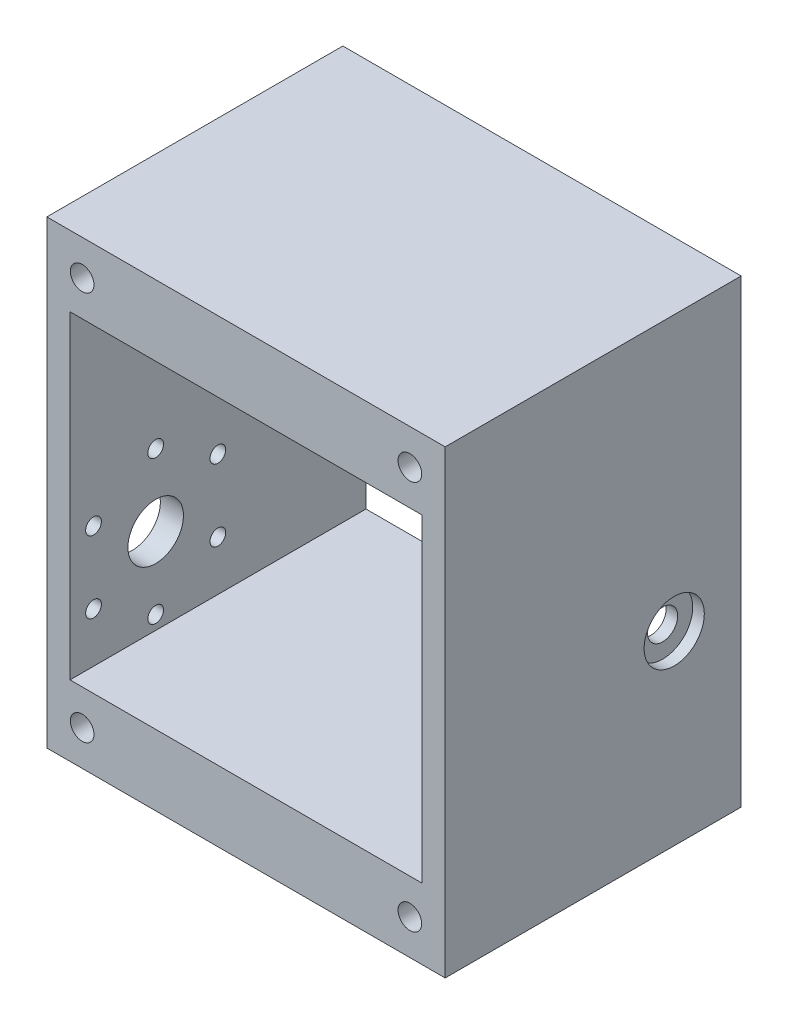
SolidWorks part; units mm, degrees
ref_plane "Front Plane" through (0, 0, 0) normal (0, 0, 1) x (1, 0, 0)
ref_plane "Top Plane" through (0, 0, 0) normal (0, 1, 0) x (1, 0, 0)
ref_plane "Right Plane" through (0, 0, 0) normal (1, 0, 0) x (0, 0, -1)
sketch "Sketch1" plane through (0, 0, 0) normal (0, 0, 1) x (1, 0, 0)
  line L1 (-43, -49.657) -> (43, -49.657)
  line L2 (-43, -49.657) -> (-43, 49.657)
  line L3 (-43, 49.657) -> (43, 49.657)
  line L4 (43, -49.657) -> (43, 49.657)
  line L5 (-43, -49.657) -> (43, 49.657) construction
  line L6 (-43, 49.657) -> (43, -49.657) construction
  point P0 (0, 0)
  dimension "D1" = 86
  dimension "D2" = 99.314
extrude "Boss-Extrude1" add sketch "Sketch1" along normal blind 63.9031
sketch "Sketch2" plane through (0, 0, 63.9031) normal (0, 0, 1) x (1, 0, 0)
  line L0 (-43, 49.657) -> (-43, -49.657) construction
  line L1 (-38, -34.417) -> (38, -34.417)
  line L2 (-38, -34.417) -> (-38, 34.417)
  line L3 (-38, 34.417) -> (38, 34.417)
  line L4 (38, -34.417) -> (38, 34.417)
  line L5 (-38, -34.417) -> (38, 34.417) construction
  line L6 (-38, 34.417) -> (38, -34.417) construction
  line L7 (43, 49.657) -> (-43, 49.657) construction
  point P0 (0, 0)
  dimension "D1" = 5
  dimension "D2" = 15.24
extrude "Cut-Extrude1" cut sketch "Sketch2" against normal through all
hole_wizard "Ø6.5 (6.5) Diameter Hole1" positions "Sketch3" profile "Sketch4" hole size "Ø6.5" standard "ANSI Metric"
sketch "Sketch3" plane through (43, 0, 0) normal (1, 0, 0) x (0, 0, -1)
  line L0 (0, -49.657) -> (0, 49.657) construction
  line L1 (0, 34.417) -> (-63.9031, 34.417) construction
  point P0 (-14.4502, -9.525)
  dimension "D1" = 14.4502
  dimension "D2" = 43.942
sketch "Sketch4" plane through (43, -9.525, 14.4502) normal (0, 1, 0) x (0, 0, -1)
  line L0 (0, 0) -> (0, 5)
  line L1 (0, 5) -> (3.25, 5)
  line L2 (3.25, 5) -> (3.25, 0)
  line L5 (3.25, 0) -> (0, 0)
  line L11 (0, -6.35) -> (0, 107.95) construction
  dimension "Thru Hole Dia." = 6.5
  dimension "Thru Hole Depth" = 5
sketch "Sketch5" plane through (-43, 0, 0) normal (-1, 0, 0) x (0, 0, 1)
  line L0 (63.9031, 49.657) -> (63.9031, -49.657) construction
  line L1 (0, -34.417) -> (63.9031, -34.417) construction
  point P0 (45.4031, -15.917)
  dimension "D1" = 18.5
  dimension "D2" = 18.5
hole_wizard "Ø12.0 (12) Diameter Hole1" positions "Sketch6" profile "Sketch7" hole size "Ø12.0" standard "ANSI Metric"
sketch "Sketch6" plane through (-43, 0, 0) normal (-1, 0, 0) x (0, 0, 1)
  point P0 (45.4031, -15.917)
sketch "Sketch7" plane through (-43, -15.917, 45.4031) normal (0, 1, 0) x (0, 0, 1)
  line L0 (0, 0) -> (0, 5)
  line L1 (0, 5) -> (6, 5)
  line L2 (6, 5) -> (6, 0)
  line L5 (6, 0) -> (0, 0)
  line L11 (0, -6.35) -> (0, 107.95) construction
  dimension "Thru Hole Dia." = 12
  dimension "Thru Hole Depth" = 5
hole_wizard "CSK for M3 Flat Head Machine Screw1" positions "Sketch8" profile "Sketch9" countersink size "M3" standard "ANSI Metric"
sketch "Sketch8" plane through (-43, 0, 0) normal (-1, 0, 0) x (0, 0, 1)
  line L0 (45.4031, -15.917) -> (45.4031, -0.417) construction
  point P0 (45.4031, -0.417)
  point P12 (58.8265, -8.167)
  point P13 (58.8265, -23.667)
  point P14 (45.4031, -31.417)
  point P15 (31.9797, -23.667)
  point P16 (31.9797, -8.167)
  dimension "D2" = 15.5
  dimension "D1" = 6
sketch "Sketch9" plane through (-43, -0.417, 45.4031) normal (0, 1, 0) x (0, 0, 1)
  line L0 (0, 0) -> (0, 5)
  line L1 (0, 5) -> (1.7, 5)
  line L2 (1.7, 5) -> (1.7, 1.45)
  line L3 (1.7, 1.45) -> (3.15, 0)
  line L5 (3.15, 0) -> (0, 0)
  line L6 (-1.7, 1.45) -> (-3.15, 0) construction
  line L11 (0, -6.35) -> (0, 107.95) construction
  dimension "Thru Hole Dia." = 3.4
  dimension "Thru Hole Depth" = 5
  dimension "Near C'Sink Dia." = 6.3
  dimension "Near C'Sink Angle" = 90
hole_wizard "#10 Clearance Hole1" positions "Sketch10" profile "Sketch11" hole size "#10" standard "ANSI Inch" end condition through all
sketch "Sketch10" plane through (0, 0, 63.9031) normal (0, 0, 1) x (1, 0, 0)
  line L0 (-43, 49.657) -> (-43, -49.657) construction
  line L1 (43, 49.657) -> (-43, 49.657) construction
  line L2 (43, -49.657) -> (43, 49.657) construction
  line L3 (-43, -49.657) -> (43, -49.657) construction
  point P0 (-35.38, 42.037)
  point P2 (35.38, 42.037)
  point P4 (-35.38, -42.037)
  point P6 (35.38, -42.037)
  dimension "D1" = 7.62
  dimension "D2" = 7.62
  dimension "D3" = 7.62
  dimension "D4" = 7.62
sketch "Sketch11" plane through (-35.38, 42.037, 63.9031) normal (1, 0, 0) x (0, -1, 0)
  line L0 (0, 0) -> (0, 63.9031)
  line L1 (0, 63.9031) -> (2.5527, 63.9031)
  line L2 (2.5527, 63.9031) -> (2.5527, 0)
  line L5 (2.5527, 0) -> (0, 0)
  line L11 (0, -6.35) -> (0, 107.95) construction
  dimension "Thru Hole Dia." = 5.1054
  dimension "Thru Hole Depth" = 63.9031
sketch "Sketch12" plane through (43, 0, 0) normal (1, 0, 0) x (0, 0, -1)
  circle A0 centre (-14.4502, -9.525) radius 6.5
  dimension "D1" = 13
extrude "Cut-Extrude2" cut sketch "Sketch12" against normal blind 2.5
equation "\"PCB Width\"= 1940mil"
equation "\"PCB Height\"= 2210mil"
equation "\"PCB Thickness\"= 63mil"
equation "\"PCB Mount Height\"= 0.25in"
equation "\"Motor Body Front Diameter\"= 37mm"
equation "\"Motor Body Front Length\"= 30mm"
equation "\"Motor Bearing Length\"= 5mm"
equation "\"Motor Body Back Length\"= 33.3mm"
equation "\"Motor PCR\"= 31mm / 2"
equation "\"Large PVC Fittings Wall Thickness\"= 15in / 64"
equation "\"Large PVC Pipe Outer Diameter\"= 3.5in"
equation "\"Box Width\"= 2 * \"Motor Bearing Length\" + \"Motor Body Front Length\" + \"Motor Body Back Length\" + 0.5in"
equation "\"Box Hole Center to Edge Distance\"= 300mil"
equation "\"Box Ceiling and Floor Thickness\"= 2 * \"Box Hole Center to Edge Distance\""
equation "\"Box Height\"= 2 * \"Box Ceiling and Floor Thickness\" + \"PCB Height\" + 0.5in"
equation "\"Box Middle Depth\"= \"Large PVC Fittings Wall Thickness\" + \"Large PVC Pipe Outer Diameter\" / 2 + \"Motor Body Front Diameter\" / 2 - \"Motor Bearing Length\""
equation "\"D1@Sketch1\"=\"Box Width\""
equation "\"D2@Sketch1\"=\"Box Height\""
equation "\"D1@Boss-Extrude1\"=\"Box Middle Depth\" "
equation "\"D1@Sketch2\"=\"Motor Bearing Length\""
equation "\"D2@Sketch2\"=\"Box Ceiling and Floor Thickness\""
equation "\"D1@Sketch3\"=\"PCB Mount Height\" + \"PCB Thickness\" + 6.5mm"
equation "\"D2@Sketch3\"=\"PCB Height\" - 0.48in"
equation "\"Motor Body Front Radius\"= \"Motor Body Front Diameter\" / 2"
equation "\"D1@Sketch5\"=\"Motor Body Front Radius\""
equation "\"D2@Sketch5\"=\"Motor Body Front Radius\""
equation "\"D2@Sketch8\"=\"Motor PCR\""
equation "\"D1@Sketch10\"=\"Box Hole Center to Edge Distance\""
equation "\"D2@Sketch10\"=\"Box Hole Center to Edge Distance\""
equation "\"D3@Sketch10\"=\"Box Hole Center to Edge Distance\""
equation "\"D4@Sketch10\"=\"Box Hole Center to Edge Distance\""
equation "\"D1@Sketch12\"=13mm"
equation "\"D1@Cut-Extrude2\"=\"Motor Bearing Length\" / 2"
